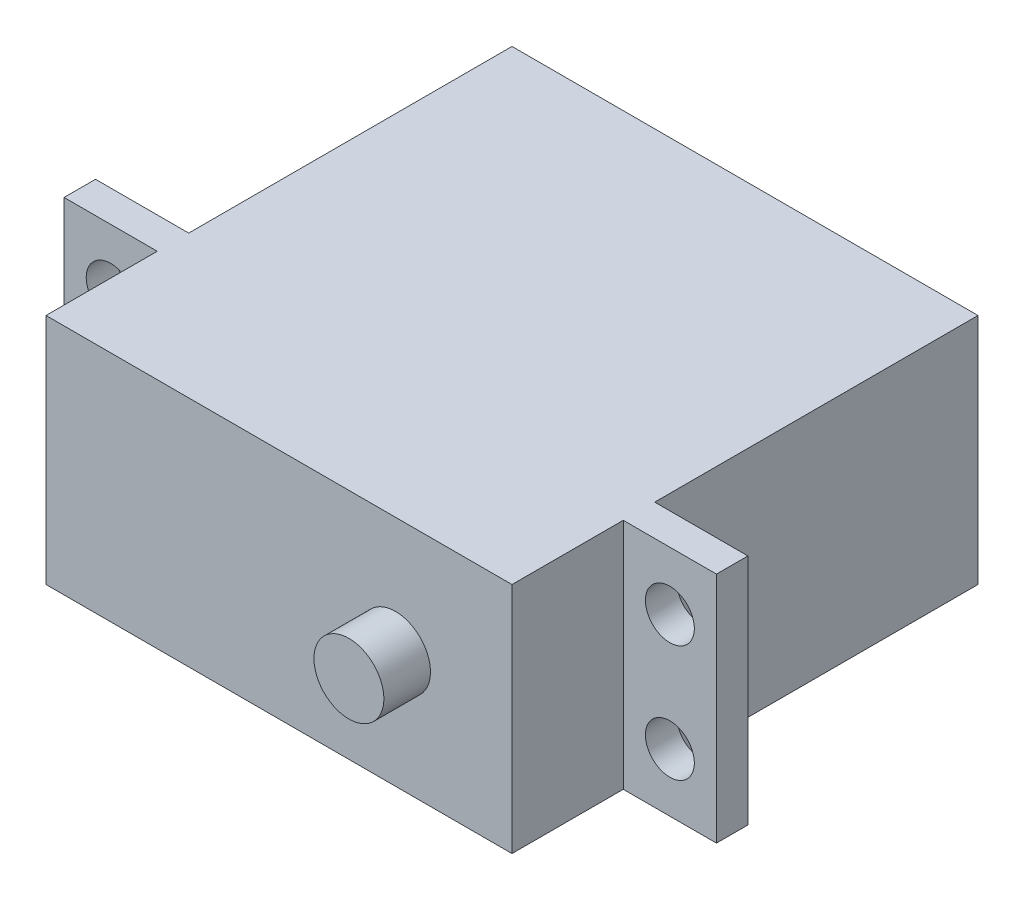
SolidWorks part; units mm, degrees
material "Custom Plastic"
ref_plane "Front Plane" through (0, 0, 0) normal (0, 0, 1) x (1, 0, 0)
ref_plane "Top Plane" through (0, 0, 0) normal (0, 1, 0) x (1, 0, 0)
ref_plane "Right Plane" through (0, 0, 0) normal (1, 0, 0) x (0, 0, -1)
sketch "Sketch1" plane through (0, 0, 0) normal (0, 0, 1) x (1, 0, 0)
  line L1 (-20, -10) -> (20, -10)
  line L2 (-20, -10) -> (-20, 10)
  line L3 (-20, 10) -> (20, 10)
  line L4 (20, -10) -> (20, 10)
  line L5 (-20, -10) -> (20, 10) construction
  line L6 (-20, 10) -> (20, -10) construction
  point P0 (0, 0)
extrude "Boss-Extrude1" add sketch "Sketch1" along normal blind 40
sketch "Sketch2" plane through (0, 0, 0) normal (0, 0, 1) x (1, 0, 0)
  line L0 (20, 0) -> (10, 0) construction
  line L1 (20, -10) -> (20, 10) construction
  line L2 (10, 0) -> (10, -10) construction
  line L3 (-20, -10) -> (20, -10) construction
  circle A0 centre (10, 0) radius 3
extrude "Boss-Extrude2" add sketch "Sketch2" along normal blind 4 from surface at 40 starting at face at (0, 0, 40)
sketch "Sketch3" plane through (0, 0, 0) normal (0, 0, 1) x (1, 0, 0)
  line L0 (-28, 0) -> (-24, 0) construction
  line L1 (-28, -10) -> (28, -10)
  line L2 (-28, -10) -> (-28, 10)
  line L3 (-28, 10) -> (28, 10)
  line L4 (28, -10) -> (28, 10)
  line L5 (-28, -10) -> (28, 10) construction
  line L6 (-28, 10) -> (28, -10) construction
  line L7 (-24, 0) -> (-24, 5) construction
  line L8 (0, 0) -> (0, 5.4036) construction
  circle A0 centre (-24, 5) radius 2.1
  circle A1 centre (-24, -5) radius 2.1
  circle A2 centre (24, -5) radius 2.1
  circle A3 centre (24, 5) radius 2.1
  point P1 (0, 0)
extrude "Boss-Extrude3" add sketch "Sketch3" along normal blind 2.7 from offset 27.75
